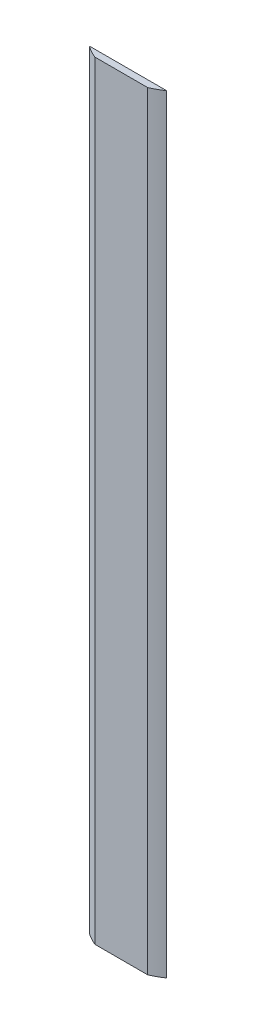
SolidWorks part; units mm, degrees
ref_plane "Front Plane" through (0, 0, 0) normal (0, 0, 1) x (1, 0, 0)
ref_plane "Top Plane" through (0, 0, 0) normal (0, 1, 0) x (1, 0, 0)
ref_plane "Right Plane" through (0, 0, 0) normal (1, 0, 0) x (0, 0, -1)
sketch "Sketch1" plane through (0, 0, 0) normal (0, 1, 0) x (1, 0, 0)
  line L0 (-12.7, -26.4729) -> (12.7, -26.4729) construction
  line L1 (-18.5439, -43.9354) -> (18.5439, -43.9354)
  line L2 (-27.1971, -39.1729) -> (27.1971, -39.1729)
  line L3 (-12.7, -35.9979) -> (12.7, -35.9979) construction
  circle A0 centre (0, 0) radius 47.6885 construction
  circle A1 centre (-12.7, -31.2354) radius 4.7625 construction
  circle A2 centre (12.7, -31.2354) radius 4.7625 construction
  circle A3 centre (12.7, -31.2354) radius 12.7 construction
  circle A4 centre (12.7, -31.2354) radius 13.97 construction
  circle A5 centre (-12.7, -31.2354) radius 12.7 construction
  circle A6 centre (-12.7, -31.2354) radius 13.97 construction
  arc A7 (-18.5439, -43.9354) -> (-27.1971, -39.1729) centre (0, 0) cw
  arc A8 (18.5439, -43.9354) -> (27.1971, -39.1729) centre (0, 0) ccw
  dimension "D1" = 95.377
  dimension "D2" = 27.94
  dimension "D3" = 25.4
  dimension "D4" = 9.525
  dimension "D5" = 3.175
  dimension "D6" = 4.7625
extrude "Boss-Extrude1" add sketch "Sketch1" along normal blind 539.75
